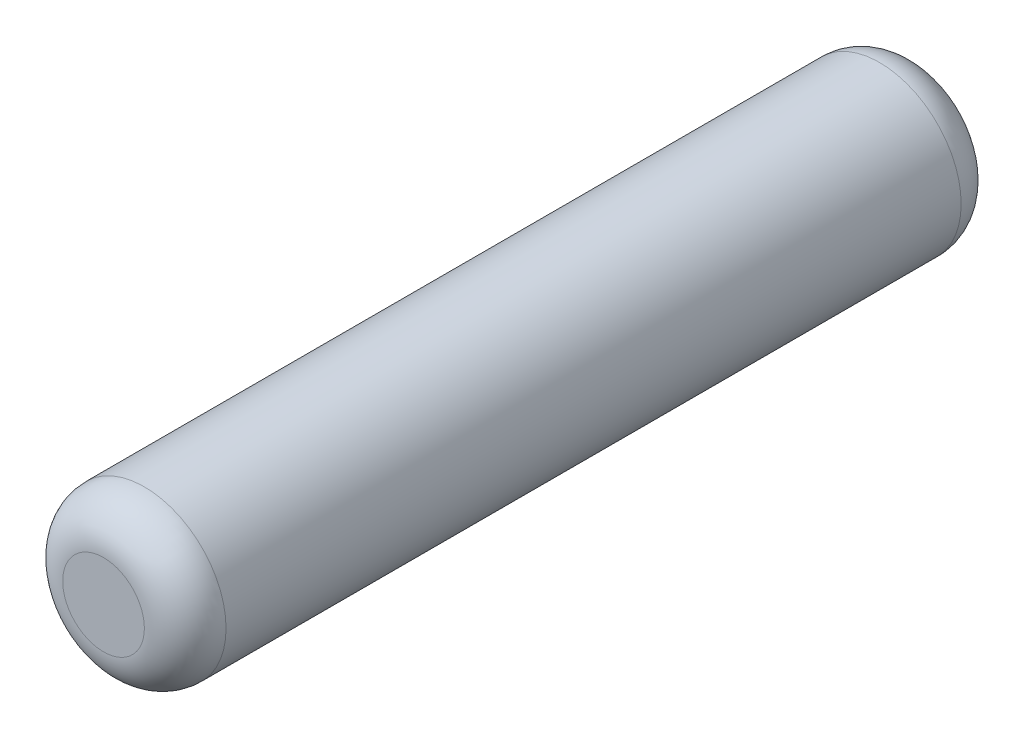
SolidWorks part; units mm, degrees
ref_plane "Plane1" through (0, 0, 0) normal (0, 0, 1) x (1, 0, 0)
ref_plane "plan de coupe 1" through (0, 0, 0) normal (0, 1, 0) x (1, 0, 0)
ref_plane "Plane3" through (0, 0, 0) normal (1, 0, 0) x (0, 0, -1)
sketch "Esquisse1" plane through (0, 0, 0) normal (0, 0, 1) x (1, 0, 0)
  circle A0 centre (0, 0) radius 2
  dimension "D1" = 4
extrude "axe" add sketch "Esquisse1" along normal blind 20
fillet "Congé" radius 1
ref_plane "plan de coupe 2" through (0, 0, 10) normal (0, 0, 1) x (1, 0, 0)
